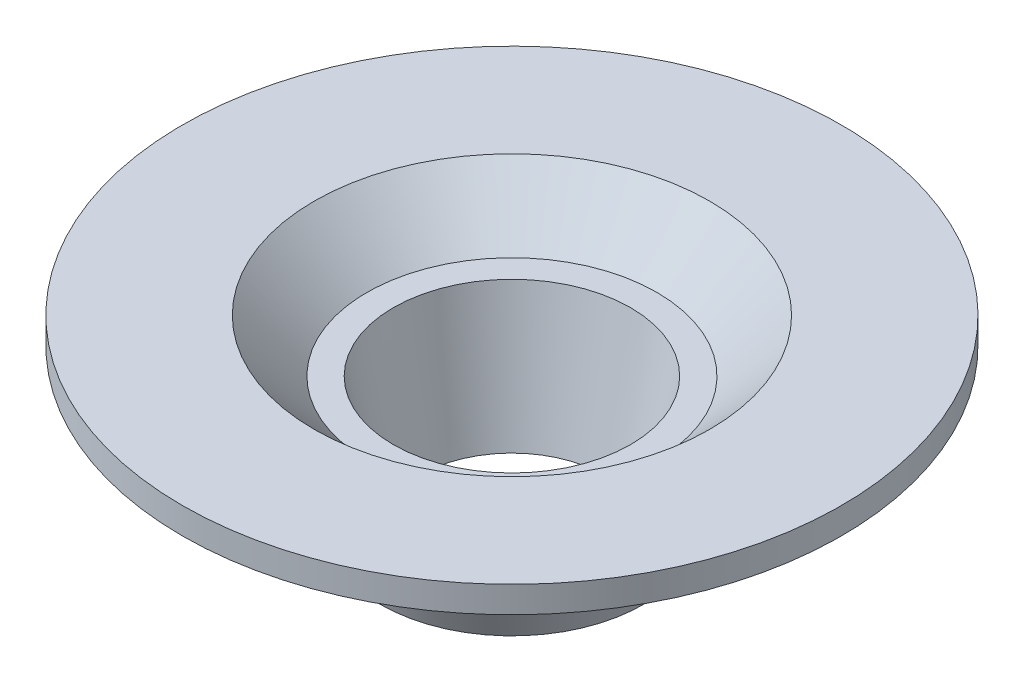
SolidWorks part; units mm, degrees
material "Titanium"
ref_plane "Front Plane" through (0, 0, 0) normal (0, 0, 1) x (1, 0, 0)
ref_plane "Top Plane" through (0, 0, 0) normal (0, 1, 0) x (1, 0, 0)
ref_plane "Right Plane" through (0, 0, 0) normal (1, 0, 0) x (0, 0, -1)
sketch "Sketch1" plane through (0, 0, 0) normal (1, 0, 0) x (0, 0, -1)
  line L0 (4.5, 0) -> (3.4969, -5)
  line L1 (3.4969, -5) -> (4.9969, -5)
  line L2 (4.9969, -5) -> (6.5, -1)
  line L3 (6.5, -1) -> (8.5, -1)
  line L4 (8.5, -1) -> (10.5, 1)
  line L5 (10.5, 1) -> (12.5, 1)
  line L6 (12.5, 1) -> (12.5, 2)
  line L7 (12.5, 2) -> (7.5, 2)
  line L8 (7.5, 2) -> (5.5, 0)
  line L9 (5.5, 0) -> (4.5, 0)
  line L10 (0, 0) -> (0, -5) construction
  dimension "D1" = 4.5
  dimension "D2" = 3.4969
  dimension "D3" = 1.5
  dimension "D4" = 6.5
  dimension "D5" = 4
  dimension "D6" = 12.5
  dimension "D7" = 5
  dimension "D8" = 2
  dimension "D9" = 2
  dimension "D10" = 1
  dimension "D11" = 2
  dimension "D12" = 1
revolve "Revolve1" add sketch "Sketch1" angle 360 about L10
